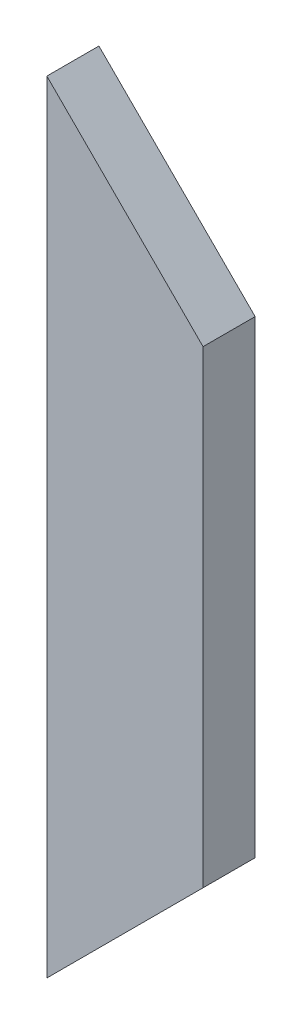
SolidWorks part; units mm, degrees
material "AISI 1020"
ref_plane "Front Plane" through (0, 0, 0) normal (0, 0, 1) x (1, 0, 0)
ref_plane "Top Plane" through (0, 0, 0) normal (0, 1, 0) x (1, 0, 0)
ref_plane "Right Plane" through (0, 0, 0) normal (1, 0, 0) x (0, 0, -1)
sketch "Sketch1" plane through (0, 0, 0) normal (0, 0, 1) x (1, 0, 0)
  line L1 (-38.1, -190.5) -> (38.1, -190.5)
  line L2 (-38.1, -190.5) -> (-38.1, 190.5)
  line L3 (-38.1, 190.5) -> (38.1, 190.5)
  line L4 (38.1, -190.5) -> (38.1, 190.5)
  line L5 (-38.1, -190.5) -> (38.1, 190.5) construction
  line L6 (-38.1, 190.5) -> (38.1, -190.5) construction
  point P0 (0, 0)
  dimension "D1" = 381
  dimension "D2" = 76.2
extrude "Boss-Extrude1" add sketch "Sketch1" along normal blind 25.4 contours L4 L3 L2 L1
sketch "Sketch2" plane through (0, 0, 25.4) normal (0, 0, 1) x (1, 0, 0)
  line L0 (-38.1, 190.5) -> (38.1, 114.3)
  line L1 (38.1, -190.5) -> (38.1, 190.5) construction
  line L2 (38.1, 114.3) -> (38.1, 190.5)
  line L3 (38.1, 190.5) -> (-38.1, 190.5)
  line L4 (-38.1, -190.5) -> (38.1, -114.3)
  line L5 (38.1, -114.3) -> (38.1, -190.5)
  line L6 (38.1, -190.5) -> (-38.1, -190.5)
  dimension "D1" = 45
  dimension "D2" = 45
extrude "Cut-Extrude1" cut sketch "Sketch2" against normal blind 25.4
equation "\"A\"= 100"
equation "\"B\"= 100"
equation "\"C\"= 100"
equation "\"D\"= 100"
equation "\"E\"= 100"
